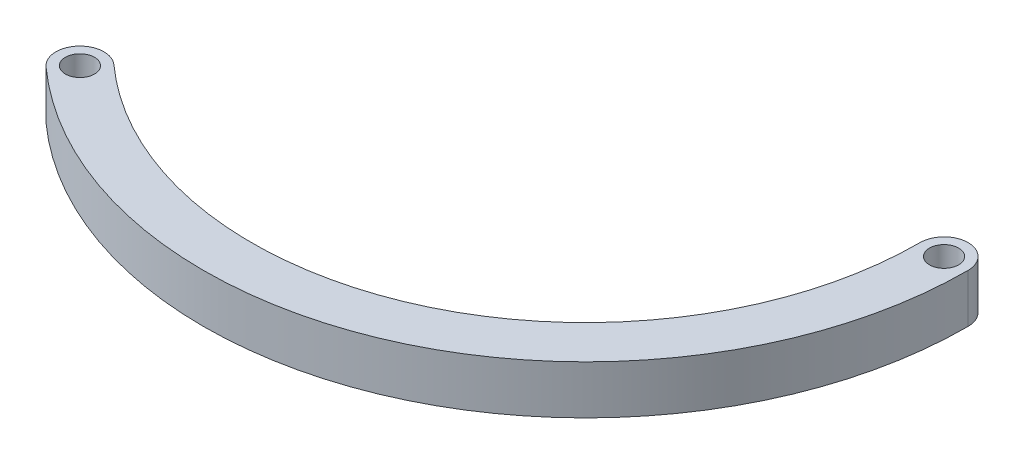
SolidWorks part; units mm, degrees
ref_plane "Front Plane" through (0, 0, 0) normal (0, 0, 1) x (1, 0, 0)
ref_plane "Top Plane" through (0, 0, 0) normal (0, 1, 0) x (1, 0, 0)
ref_plane "Right Plane" through (0, 0, 0) normal (1, 0, 0) x (0, 0, -1)
sketch "Sketch1" plane through (0, 0, 0) normal (0, 1, 0) x (1, 0, 0)
  circle A0 centre (0, 0) radius 39.35
  dimension "D1" = 78.7
extrude "Boss-Extrude1" add sketch "Sketch1" along normal blind 5
sketch "Sketch2" plane through (0, 5, 0) normal (0, 1, 0) x (1, 0, 0)
  circle A0 centre (0, 0) radius 34.4
  dimension "D1" = 68.8
extrude "Cut-Extrude1" cut sketch "Sketch2" against normal blind 5
sketch "Sketch4" plane through (0, 5, 0) normal (0, 1, 0) x (1, 0, 0)
  line L0 (-26.2756, -29.2919) -> (0, 0)
  line L1 (0, 0) -> (39.35, 0.0221)
  arc A0 (39.35, 0.0221) -> (-26.2756, -29.2919) centre (0, 0) cw
  circle A1 centre (0, 0) radius 39.35 construction
  arc A2 (-26.2756, -29.2919) -> (39.35, 0) centre (0, 0) ccw
  circle M1 centre (0, 0) radius 34.4
  circle M2 centre (0, 0) radius 39.35
extrude "Cut-Extrude2" cut sketch "Sketch4" against normal blind 5 contours L1 L0 M1 M2
sketch "Sketch9" plane through (0, 5, 0) normal (0, 1, 0) x (1, 0, 0)
  line L0 (34.4, 0.0193) -> (39.35, 0.0221) construction
  line L3 (-22.9703, -25.6072) -> (-26.2756, -29.2919)
  line L4 (39.35, 0.0221) -> (34.4, 0.0193)
  line L5 (-22.9703, -25.6072) -> (-26.2756, -29.2919)
  arc A0 (34.4, 0.0193) -> (39.35, 0.0221) centre (36.875, 0.0207) cw
  arc A4 (-26.2756, -29.2919) -> (39.35, 0.0221) centre (0, 0) ccw
  arc A5 (-22.9703, -25.6072) -> (34.4, 0.0193) centre (0, 0) ccw
  arc A6 (-26.2756, -29.2919) -> (39.35, 0.0221) centre (0, 0) ccw
  arc A7 (-22.9703, -25.6072) -> (34.4, 0.0193) centre (0, 0) ccw
  dimension "D1" = 0
extrude "Boss-Extrude2" add sketch "Sketch9" against normal blind 5
sketch "Sketch10" plane through (0, 5, 0) normal (0, 1, 0) x (1, 0, 0)
  line L0 (-26.2756, -29.2919) -> (-22.9703, -25.6072) construction
  line L2 (-22.9703, -25.6072) -> (-26.2756, -29.2919)
  arc A0 (-26.2756, -29.2919) -> (-22.9703, -25.6072) centre (-24.6229, -27.4495) cw
  arc A5 (-26.2756, -29.2919) -> (39.35, 0.0221) centre (0, 0) ccw
  arc A6 (39.35, 0.0221) -> (34.4, 0.0193) centre (36.875, 0.0207) ccw
  arc A7 (-22.9703, -25.6072) -> (34.4, 0.0193) centre (0, 0) ccw
  arc A8 (-26.2756, -29.2919) -> (39.35, 0.0221) centre (0, 0) ccw
  arc A9 (39.35, 0.0221) -> (34.4, 0.0193) centre (36.875, 0.0207) ccw
  arc A10 (-22.9703, -25.6072) -> (34.4, 0.0193) centre (0, 0) ccw
  dimension "D1" = 0
extrude "Boss-Extrude3" add sketch "Sketch10" against normal blind 5
sketch "Sketch11" plane through (0, 5, 0) normal (0, 1, 0) x (1, 0, 0)
  circle A0 centre (-24.6229, -27.4495) radius 1.5
  dimension "D1" = 3
extrude "Cut-Extrude3" cut sketch "Sketch11" against normal blind 5
sketch "Sketch12" plane through (0, 5, 0) normal (0, 1, 0) x (1, 0, 0)
  circle A0 centre (36.875, 0.0207) radius 1.5
  dimension "D1" = 3
extrude "Cut-Extrude4" cut sketch "Sketch12" against normal blind 5
